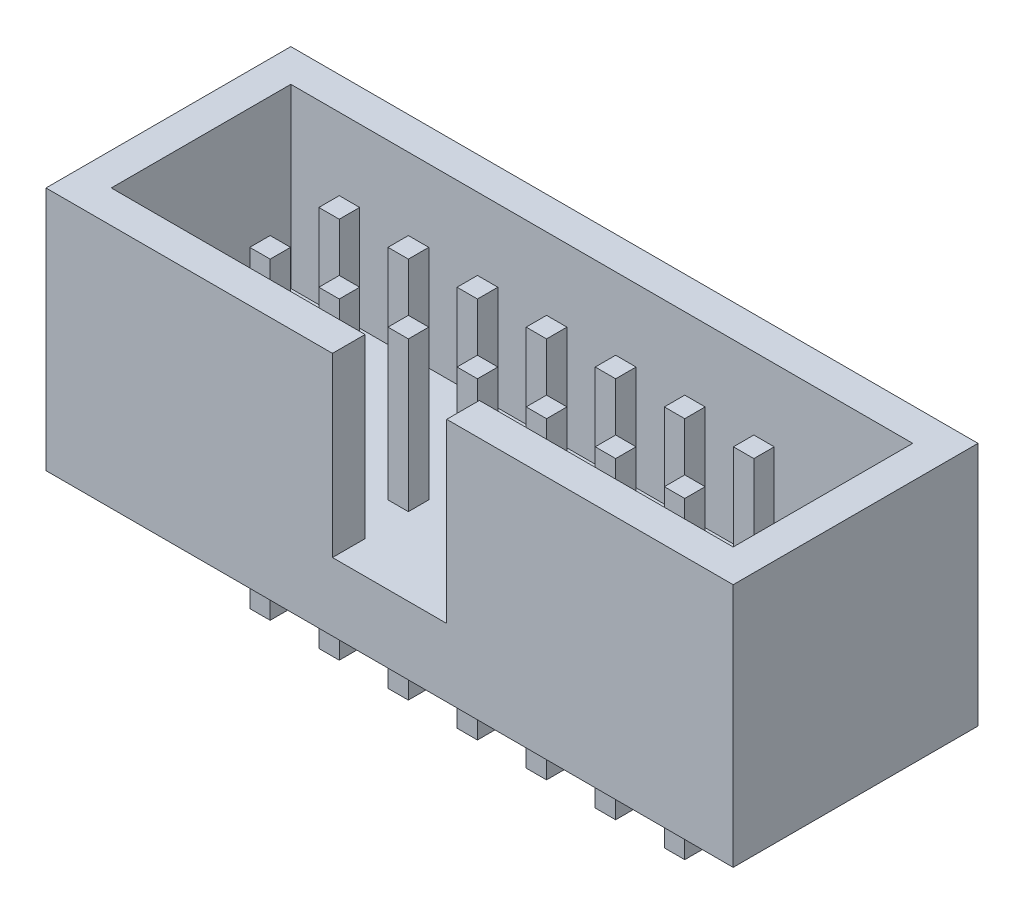
SolidWorks part; units mm, degrees
ref_plane "前视基准面" through (0, 0, 0) normal (0, 0, 1) x (1, 0, 0)
ref_plane "上视基准面" through (0, 0, 0) normal (0, 1, 0) x (1, 0, 0)
ref_plane "右视基准面" through (0, 0, 0) normal (1, 0, 0) x (0, 0, -1)
sketch "草图1" plane through (0, 0, 0) normal (0, 1, 0) x (1, 0, 0)
  line L0 (0, 85.0964) -> (0, -118.2031) construction
  line L1 (-12.63, 4.5) -> (12.63, 4.5)
  line L2 (-12.63, 4.5) -> (-12.63, -4.5)
  line L3 (-12.63, -4.5) -> (12.63, -4.5)
  line L4 (12.63, 4.5) -> (12.63, -4.5)
  line L5 (-200.5452, 0) -> (261.2352, 0) construction
  dimension "D1" = 9
  dimension "D2" = 25.26
extrude "拉伸1" add sketch "草图1" along normal blind 9
sketch "草图2" plane through (0, 9, 0) normal (0, 1, 0) x (-1, 0, 0)
  line L8 (-11.43, 3.3) -> (-11.43, -3.3)
  line L9 (11.43, 3.3) -> (-11.43, 3.3)
  line L10 (11.43, -3.3) -> (11.43, 3.3)
  line L11 (-11.43, -3.3) -> (11.43, -3.3)
  line L12 (-11.43, 3.3) -> (-11.43, -3.3)
  line L13 (11.43, 3.3) -> (-11.43, 3.3)
  line L14 (11.43, -3.3) -> (11.43, 3.3)
  line L15 (-11.43, -3.3) -> (11.43, -3.3)
  dimension "D1" = 1.2
extrude "切除-拉伸1" cut sketch "草图2" against normal blind 6.5
sketch "草图3" plane through (0, 0, 4.5) normal (0, 0, 1) x (1, 0, 0)
  line L0 (-12.63, 9) -> (12.63, 9) construction
  line L1 (-2.1, 9) -> (2.1, 9)
  line L2 (-2.1, 9) -> (-2.1, 2.5)
  line L3 (-2.1, 2.5) -> (2.1, 2.5)
  line L4 (2.1, 9) -> (2.1, 2.5)
  line L5 (-11.43, 2.5) -> (11.43, 2.5) construction
  line L6 (0, 9.4226) -> (0, -4.0288) construction
  dimension "D1" = 4.2
extrude "切除-拉伸2" cut sketch "草图3" against normal blind 6.5
sketch "草图5" plane through (0, 0, 0) normal (0, -1, 0) x (1, 0, 0)
  line L0 (0, 6.0683) -> (0, -6.9786) construction
  line L1 (-21.1981, 0) -> (21.4095, 0) construction
  line L2 (-2.4898, 1.27) -> (1.0953, 1.27) construction
  line L3 (-0.375, 0.895) -> (0.375, 0.895)
  line L4 (-0.375, 0.895) -> (-0.375, 1.645)
  line L5 (-0.375, 1.645) -> (0.375, 1.645)
  line L6 (0.375, 0.895) -> (0.375, 1.645)
  line L7 (2.165, 0.895) -> (2.915, 0.895)
  line L8 (2.165, 0.895) -> (2.165, 1.645)
  line L9 (2.165, 1.645) -> (2.915, 1.645)
  line L10 (2.915, 0.895) -> (2.915, 1.645)
  line L11 (4.705, 0.895) -> (5.455, 0.895)
  line L12 (4.705, 0.895) -> (4.705, 1.645)
  line L13 (4.705, 1.645) -> (5.455, 1.645)
  line L14 (5.455, 0.895) -> (5.455, 1.645)
  line L15 (7.245, 0.895) -> (7.995, 0.895)
  line L16 (7.245, 0.895) -> (7.245, 1.645)
  line L17 (7.245, 1.645) -> (7.995, 1.645)
  line L18 (7.995, 0.895) -> (7.995, 1.645)
  line L31 (-2.915, 0.895) -> (-2.165, 0.895)
  line L32 (-2.915, 0.895) -> (-2.915, 1.645)
  line L33 (-2.915, 1.645) -> (-2.165, 1.645)
  line L34 (-2.165, 0.895) -> (-2.165, 1.645)
  line L35 (-5.455, 0.895) -> (-4.705, 0.895)
  line L36 (-5.455, 0.895) -> (-5.455, 1.645)
  line L37 (-5.455, 1.645) -> (-4.705, 1.645)
  line L38 (-4.705, 0.895) -> (-4.705, 1.645)
  line L39 (-7.995, 0.895) -> (-7.245, 0.895)
  line L40 (-7.995, 0.895) -> (-7.995, 1.645)
  line L41 (-7.995, 1.645) -> (-7.245, 1.645)
  line L42 (-7.245, 0.895) -> (-7.245, 1.645)
  line L55 (-2.4898, -1.27) -> (1.0953, -1.27) construction
  line L68 (-7.245, -0.895) -> (-7.245, -1.645)
  line L69 (-7.995, -1.645) -> (-7.245, -1.645)
  line L70 (-7.995, -0.895) -> (-7.995, -1.645)
  line L71 (-7.995, -0.895) -> (-7.245, -0.895)
  line L72 (-4.705, -0.895) -> (-4.705, -1.645)
  line L73 (-5.455, -1.645) -> (-4.705, -1.645)
  line L74 (-5.455, -0.895) -> (-5.455, -1.645)
  line L75 (-5.455, -0.895) -> (-4.705, -0.895)
  line L76 (-2.165, -0.895) -> (-2.165, -1.645)
  line L77 (-2.915, -1.645) -> (-2.165, -1.645)
  line L78 (-2.915, -0.895) -> (-2.915, -1.645)
  line L79 (-2.915, -0.895) -> (-2.165, -0.895)
  line L92 (7.995, -0.895) -> (7.995, -1.645)
  line L93 (7.245, -1.645) -> (7.995, -1.645)
  line L94 (7.245, -0.895) -> (7.245, -1.645)
  line L95 (7.245, -0.895) -> (7.995, -0.895)
  line L96 (5.455, -0.895) -> (5.455, -1.645)
  line L97 (4.705, -1.645) -> (5.455, -1.645)
  line L98 (4.705, -0.895) -> (4.705, -1.645)
  line L99 (4.705, -0.895) -> (5.455, -0.895)
  line L100 (2.915, -0.895) -> (2.915, -1.645)
  line L101 (2.165, -1.645) -> (2.915, -1.645)
  line L102 (2.165, -0.895) -> (2.165, -1.645)
  line L103 (2.165, -0.895) -> (2.915, -0.895)
  line L104 (0.375, -0.895) -> (0.375, -1.645)
  line L105 (-0.375, -1.645) -> (0.375, -1.645)
  line L106 (-0.375, -0.895) -> (-0.375, -1.645)
  line L107 (-0.375, -0.895) -> (0.375, -0.895)
  dimension "D1" = 0.75
  dimension "D2" = 0.75
  dimension "D3" = 1.27
extrude "拉伸2" add sketch "草图5" along normal blind 3.5 and the other way offset from surface (8 mm away) 1 other way up to face at (0, 9, 1.3)
